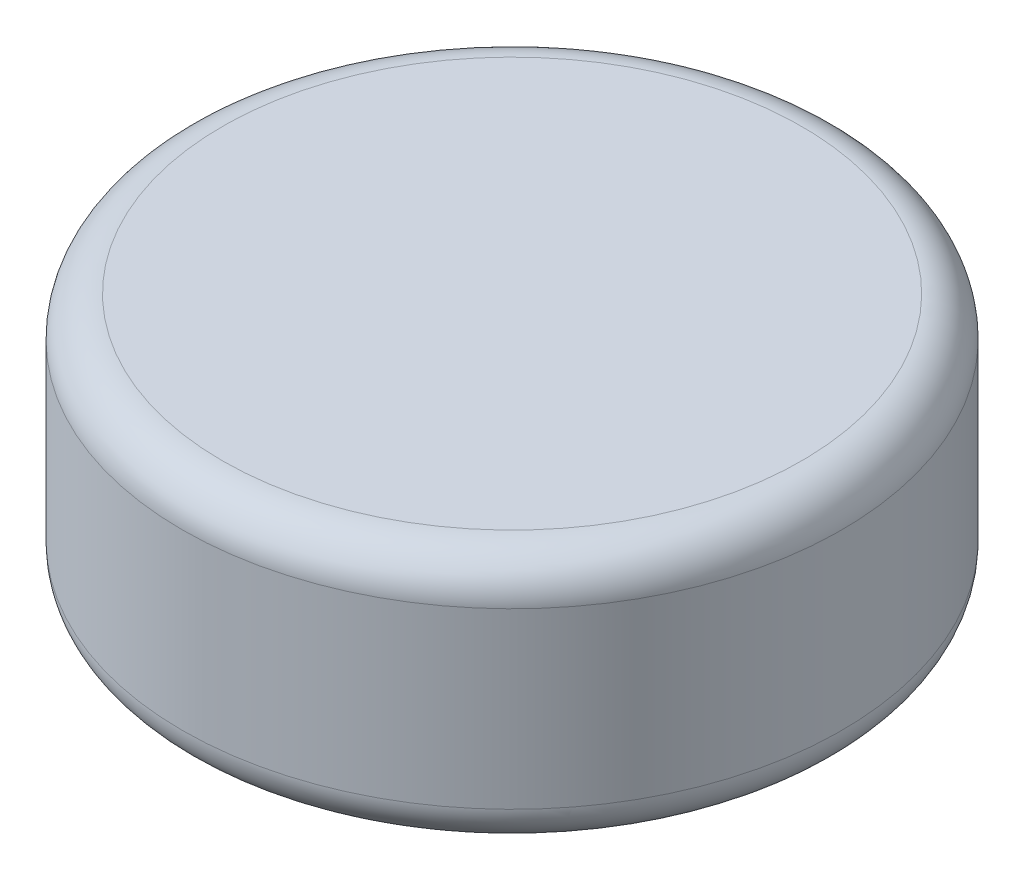
SolidWorks part; units mm, degrees
ref_plane "Piano frontale" through (0, 0, 0) normal (1, 0, 0) x (0, 1, 0)
ref_plane "Piano superiore" through (0, 0, 0) normal (0, 0, 1) x (0, 1, 0)
ref_plane "Piano destro" through (0, 0, 0) normal (0, 1, 0) x (-1, 0, 0)
sketch "Schizzo1" plane through (0, 0, 0) normal (0, 1, 0) x (-1, 0, 0)
  circle A0 centre (0, 0) radius 330.2
  dimension "D1" = 660.4
extrude "Estrusione-Estrusione1" add sketch "Schizzo1" along normal blind 254 contours A0
fillet "Raccordo1" radius 40 2 edges at (0, 0, 330.2) (0, 254, 330.2)
